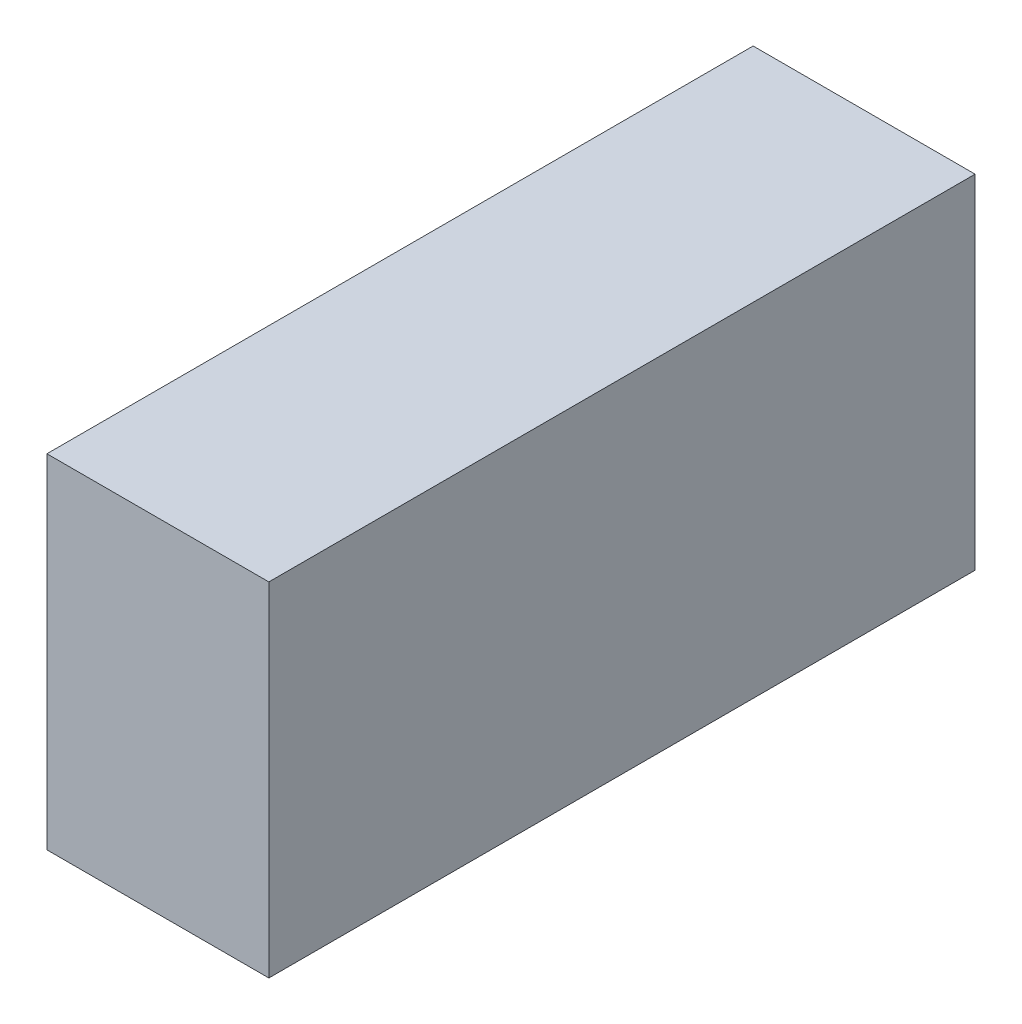
SolidWorks part; units mm, degrees
material "Batery"
ref_plane "Plano frontal" through (0, 0, 0) normal (0, 0, 1) x (1, 0, 0)
ref_plane "Plano superior" through (0, 0, 0) normal (0, 1, 0) x (1, 0, 0)
ref_plane "Plano direito" through (0, 0, 0) normal (1, 0, 0) x (0, 0, -1)
sketch "Sketch1" plane through (0, 0, 0) normal (0, 0, 1) x (1, 0, 0)
  line L1 (-11, -17) -> (11, -17)
  line L2 (-11, -17) -> (-11, 17)
  line L3 (-11, 17) -> (11, 17)
  line L4 (11, -17) -> (11, 17)
  line L5 (-11, -17) -> (11, 17) construction
  line L6 (-11, 17) -> (11, -17) construction
  point P0 (0, 0)
  dimension "D1" = 22
  dimension "D2" = 34
extrude "Boss-Extrude1" add sketch "Sketch1" along normal mid plane 70
